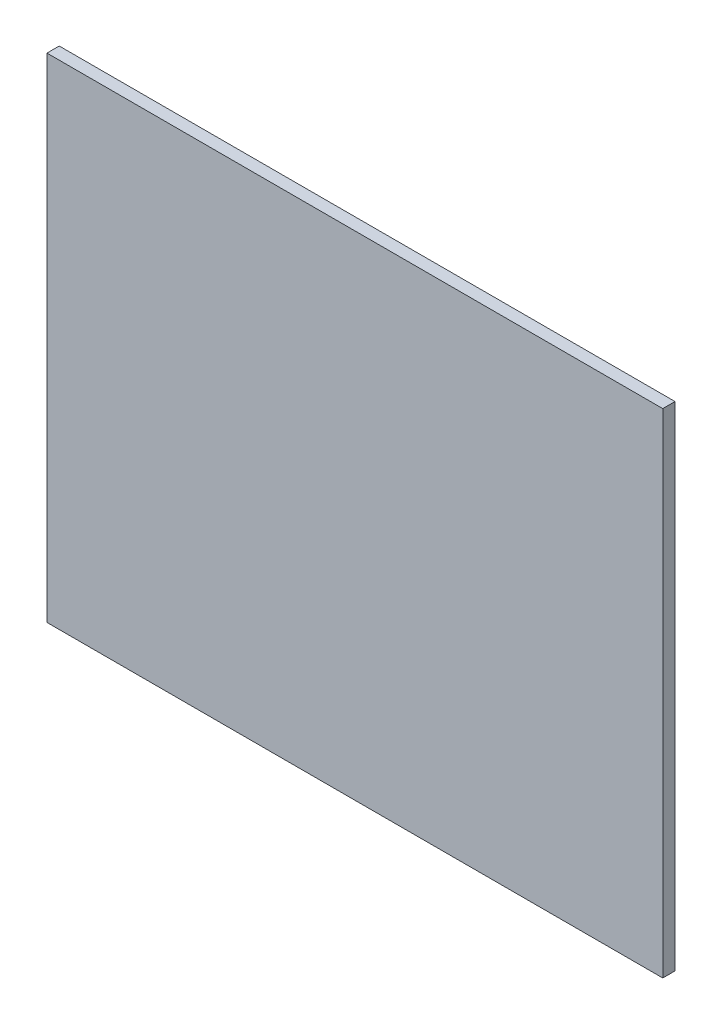
SolidWorks part; units mm, degrees
ref_plane "Front Plane" through (0, 0, 0) normal (0, 0, 1) x (1, 0, 0)
ref_plane "Top Plane" through (0, 0, 0) normal (0, 1, 0) x (1, 0, 0)
ref_plane "Right Plane" through (0, 0, 0) normal (1, 0, 0) x (0, 0, -1)
sketch "Sketch4" [suppressed] plane through (0, 5, 0) normal (0, 1, 0) x (1, 0, 0)
  line L0 (68.7773, 9.2084) -> (148.7773, 9.2084)
  line L1 (-6.2227, 50.3605) -> (223.7773, 50.3605)
  line L2 (148.7773, 9.2084) -> (148.7773, 83.5404)
  line L3 (148.7773, 83.5404) -> (68.7773, 83.5404)
  line L4 (108.7773, 83.5404) -> (108.7773, 17.1805) construction
  line L5 (68.7773, 9.2084) -> (68.7773, 83.5404)
  line L6 (-6.2227, 4375.9414) -> (-6.2227, 4095.9414) construction
  line L7 (223.7773, 4095.9414) -> (223.7773, 4375.9414) construction
  point P12 (108.7773, 50.3605)
  dimension "D1" = 80
extrude "Cut-Extrude1" [suppressed] cut sketch "Sketch4" against normal blind 10
sketch "Sketch5" plane through (0, 0, 0) normal (0, 0, 1) x (1, 0, 0)
  line L1 (0, 0) -> (251, 0)
  line L2 (0, 0) -> (0, 201)
  line L3 (0, 201) -> (251, 201)
  line L4 (251, 0) -> (251, 201)
  dimension "D1" = 251
  dimension "D2" = 201
extrude "Boss-Extrude2" add sketch "Sketch5" along normal blind 5
